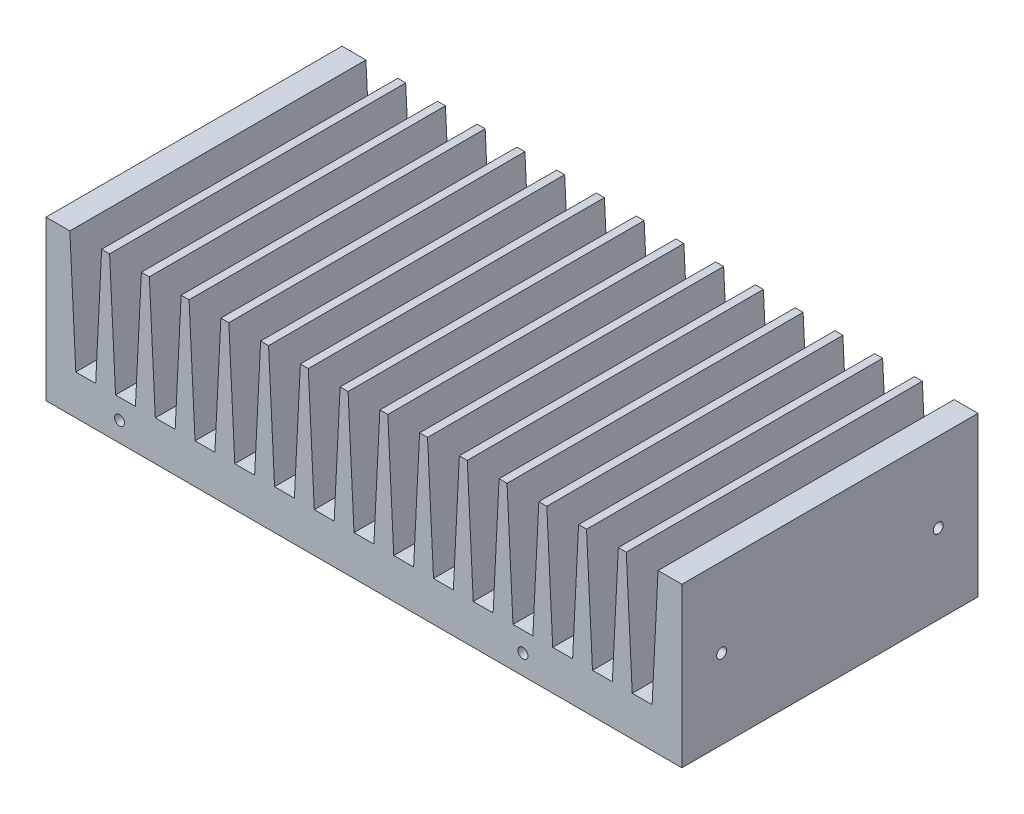
SolidWorks part; units mm, degrees
ref_plane "Front Plane" through (0, 0, 0) normal (0, 0, 1) x (1, 0, 0)
ref_plane "Top Plane" through (0, 0, 0) normal (0, 1, 0) x (1, 0, 0)
ref_plane "Right Plane" through (0, 0, 0) normal (1, 0, 0) x (0, 0, -1)
sketch "Sketch1" plane through (0, 0, 0) normal (0, 0, 1) x (1, 0, 0)
  line L0 (0, 0) -> (0, 40)
  line L1 (0, 0) -> (160, 0)
  line L2 (160, 40) -> (160, 0)
  line L3 (-34.4404, 10) -> (178.0829, 10) construction
  line L4 (0, 40) -> (6, 40)
  line L5 (6, 40) -> (7.5, 10)
  line L6 (7.5, 10) -> (12.5, 10)
  line L7 (12.5, 10) -> (14, 40)
  line L8 (14, 40) -> (16, 40)
  line L9 (16, 40) -> (17.5, 10)
  line L10 (26, 40) -> (27.5, 10)
  line L11 (24, 40) -> (26, 40)
  line L12 (22.5, 10) -> (24, 40)
  line L13 (17.5, 10) -> (22.5, 10)
  line L14 (36, 40) -> (37.5, 10)
  line L15 (34, 40) -> (36, 40)
  line L16 (32.5, 10) -> (34, 40)
  line L17 (27.5, 10) -> (32.5, 10)
  line L18 (46, 40) -> (47.5, 10)
  line L19 (44, 40) -> (46, 40)
  line L20 (42.5, 10) -> (44, 40)
  line L21 (37.5, 10) -> (42.5, 10)
  line L22 (56, 40) -> (57.5, 10)
  line L23 (54, 40) -> (56, 40)
  line L24 (52.5, 10) -> (54, 40)
  line L25 (47.5, 10) -> (52.5, 10)
  line L26 (66, 40) -> (67.5, 10)
  line L27 (64, 40) -> (66, 40)
  line L28 (62.5, 10) -> (64, 40)
  line L29 (57.5, 10) -> (62.5, 10)
  line L30 (76, 40) -> (77.5, 10)
  line L31 (74, 40) -> (76, 40)
  line L32 (72.5, 10) -> (74, 40)
  line L33 (67.5, 10) -> (72.5, 10)
  line L34 (86, 40) -> (87.5, 10)
  line L35 (84, 40) -> (86, 40)
  line L36 (82.5, 10) -> (84, 40)
  line L37 (77.5, 10) -> (82.5, 10)
  line L38 (96, 40) -> (97.5, 10)
  line L39 (94, 40) -> (96, 40)
  line L40 (92.5, 10) -> (94, 40)
  line L41 (87.5, 10) -> (92.5, 10)
  line L42 (106, 40) -> (107.5, 10)
  line L43 (104, 40) -> (106, 40)
  line L44 (102.5, 10) -> (104, 40)
  line L45 (97.5, 10) -> (102.5, 10)
  line L46 (116, 40) -> (117.5, 10)
  line L47 (114, 40) -> (116, 40)
  line L48 (112.5, 10) -> (114, 40)
  line L49 (107.5, 10) -> (112.5, 10)
  line L50 (126, 40) -> (127.5, 10)
  line L51 (124, 40) -> (126, 40)
  line L52 (122.5, 10) -> (124, 40)
  line L53 (117.5, 10) -> (122.5, 10)
  line L54 (136, 40) -> (137.5, 10)
  line L55 (134, 40) -> (136, 40)
  line L56 (132.5, 10) -> (134, 40)
  line L57 (127.5, 10) -> (132.5, 10)
  line L58 (146, 40) -> (147.5, 10)
  line L59 (144, 40) -> (146, 40)
  line L60 (142.5, 10) -> (144, 40)
  line L61 (137.5, 10) -> (142.5, 10)
  line L62 (147.5, 10) -> (152.5, 10)
  line L63 (152.5, 10) -> (154, 40)
  line L64 (154, 40) -> (160, 40)
  dimension "D1" = 160
  dimension "D2" = 40
  dimension "D3" = 40
  dimension "D4" = 10
  dimension "D5" = 6
  dimension "D6" = 7.5
  dimension "D7" = 5
  dimension "D8" = 5
  dimension "D9" = 2
  dimension "D10" = 1.5
  dimension "D12" = 5
  dimension "D13" = 6
  dimension "D11" = 14
extrude "Boss-Extrude1" add sketch "Sketch1" along normal blind 74.5
sketch "Sketch2" plane through (160, 0, 0) normal (1, 0, 0) x (0, 0, -1)
  line L0 (-74.5, 0) -> (-74.5, 40) construction
  line L1 (0, 0) -> (0, 40) construction
  line L2 (-74.5, 40) -> (0, 40) construction
  circle A0 centre (-64.5, 20) radius 1.25
  circle A1 centre (-10, 20) radius 1.25
  dimension "D1" = 2.5
  dimension "D2" = 2.5
  dimension "D3" = 10
  dimension "D4" = 10
  dimension "D5" = 20
  dimension "D6" = 20
extrude "Cut-Extrude1" cut sketch "Sketch2" against normal blind 10
sketch "Sketch3" plane through (0, 0, 0) normal (-1, 0, 0) x (0, 0, 1)
  line L0 (74.5, 40) -> (0, 40) construction
  line L1 (0, 40) -> (0, 0) construction
  line L2 (74.5, 40) -> (74.5, 0) construction
  circle A0 centre (20, 20) radius 1.25
  circle A1 centre (54.5, 20) radius 1.25
  dimension "D1" = 2.5
  dimension "D2" = 2.5
  dimension "D3" = 20
  dimension "D4" = 20
  dimension "D5" = 20
  dimension "D6" = 20
extrude "Cut-Extrude2" cut sketch "Sketch3" against normal blind 10
sketch "Sketch4" plane through (0, 0, 74.5) normal (0, 0, 1) x (1, 0, 0)
  circle A0 centre (18.5, 5) radius 1.25
  circle A1 centre (120, 5) radius 1.25
  dimension "D1" = 2.5
  dimension "D2" = 2.5
extrude "Cut-Extrude3" cut sketch "Sketch4" against normal blind 15
sketch "Sketch5" plane through (0, 0, 0) normal (0, 0, -1) x (-1, 0, 0)
  circle A0 centre (-120, 5) radius 1.25
  circle A1 centre (-18.5, 5) radius 1.25
  dimension "D1" = 2.5
  dimension "D2" = 2.5
extrude "Cut-Extrude4" cut sketch "Sketch5" against normal blind 15
